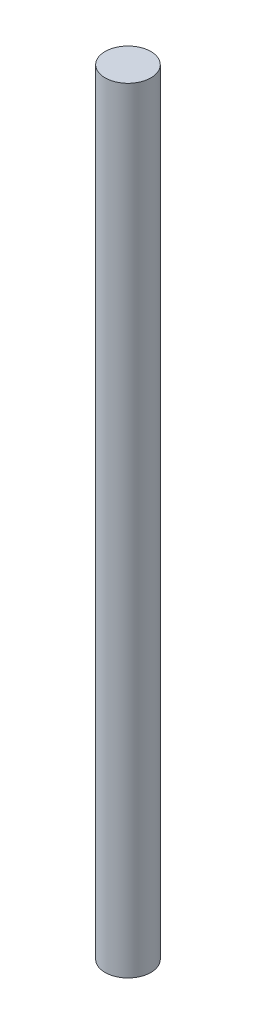
SolidWorks part; units mm, degrees
ref_plane "Front Plane" through (0, 0, 0) normal (0, 0, 1) x (1, 0, 0)
ref_plane "Top Plane" through (0, 0, 0) normal (0, 1, 0) x (1, 0, 0)
ref_plane "Right Plane" through (0, 0, 0) normal (1, 0, 0) x (0, 0, -1)
sketch "Sketch1" plane through (0, 0, 0) normal (0, 1, 0) x (1, 0, 0)
  circle A0 centre (0, 0) radius 10
  dimension "D1" = 20
extrude "Boss-Extrude1" add sketch "Sketch1" along normal blind 339
